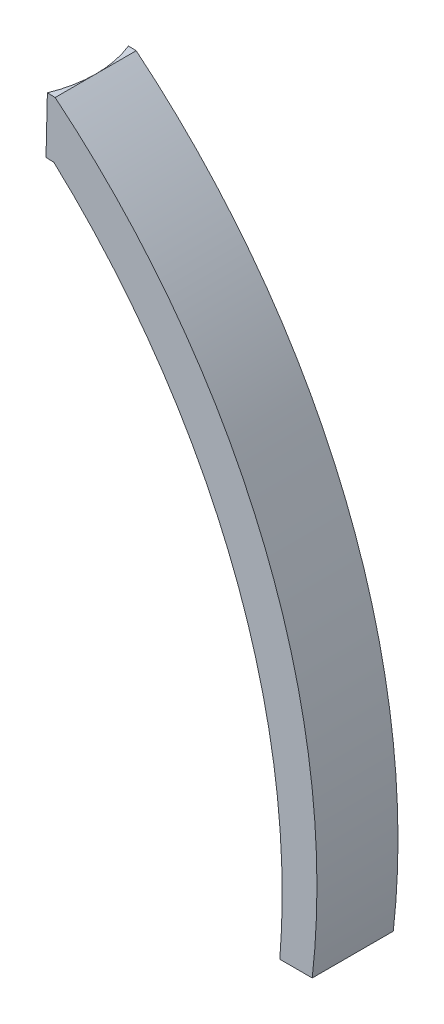
SolidWorks part; units mm, degrees
ref_plane "Front Plane" through (0, 0, 0) normal (0, 0, 1) x (1, 0, 0)
ref_plane "Top Plane" through (0, 0, 0) normal (0, 1, 0) x (1, 0, 0)
ref_plane "Right Plane" through (0, 0, 0) normal (1, 0, 0) x (0, 0, -1)
sketch "Sketch1" plane through (0, 0, 0) normal (0, 0, 1) x (1, 0, 0)
  line L0 (-18.7574, 33.4181) -> (-20.6341, -44.8119) construction
  line L1 (-20.6341, -44.8119) -> (12.9659, -44.8119) construction
  line L2 (-18.7574, 33.4181) -> (-18.9254, 26.4181)
  line L3 (8.9659, -44.8119) -> (12.9659, -44.8119)
  arc A0 (-18.9254, 26.4181) -> (8.9659, -44.8119) centre (-77.7419, -37.6881) cw
  arc A1 (-18.7574, 33.4181) -> (12.9659, -44.8119) centre (-74.4528, -34.7143) cw
  point P2 (8.9659, -44.8119)
  point P4 (-18.9254, 26.4181)
  dimension "D5" = 87
  dimension "D6" = 88
  dimension "D1" = 71.23
  dimension "D2" = 33.6
  dimension "D3" = 4
  dimension "D4" = 7
extrude "Boss-Extrude1" add sketch "Sketch1" along normal blind 10
ref_plane "Plane1" through (0.7904, 32.9492, 0) normal (0.024, 0.9997, 0) x (0, 0, -1)
sketch "Sketch2" plane through (0.7904, 32.9492, 0) normal (0.024, 0.9997, 0) x (0, 0, -1)
  line L0 (-5, 19.5535) -> (-5, 33.0535) construction
  line L1 (-10, 19.5535) -> (0, 19.5535) construction
  line L7 (-10, 19.5535) -> (-10, 20.5135)
  line L8 (-10, 19.5535) -> (-5, 19.5535)
  line L9 (0, 19.5535) -> (0, 20.5135)
  line L10 (0, 19.5535) -> (-5, 19.5535)
  arc A0 (-10, 20.5135) -> (0, 20.5135) centre (-5, 33.0535) ccw
  arc A1 (-10, 20.5135) -> (0, 20.5135) centre (-5, 33.0535) ccw
  dimension "D1" = 13.5
extrude "Boss-Extrude2" add sketch "Sketch2" against normal blind 7 contours A0 L7 L8 | A0 L10 L9
